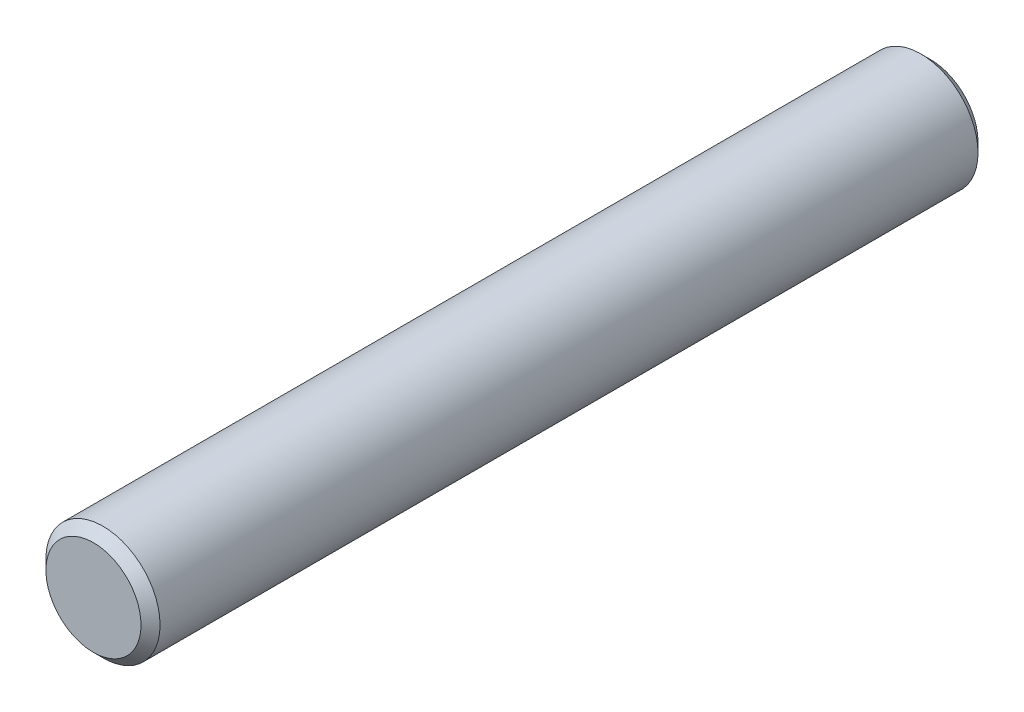
SolidWorks part; units mm, degrees
ref_plane "Front Plane" through (0, 0, 0) normal (0, 0, 1) x (1, 0, 0)
ref_plane "Top Plane" through (0, 0, 0) normal (0, 1, 0) x (1, 0, 0)
ref_plane "Right Plane" through (0, 0, 0) normal (1, 0, 0) x (0, 0, -1)
sketch "Sketch1" plane through (0, 0, 0) normal (0, 0, 1) x (1, 0, 0)
  circle A0 centre (0, 0) radius 3
  dimension "D1" = 6
extrude "Boss-Extrude1" add sketch "Sketch1" along normal blind 44
chamfer "Chamfer1" distance 0.5 angle 45 2 edges at (3, 0, 0) (3, 0, 44)
